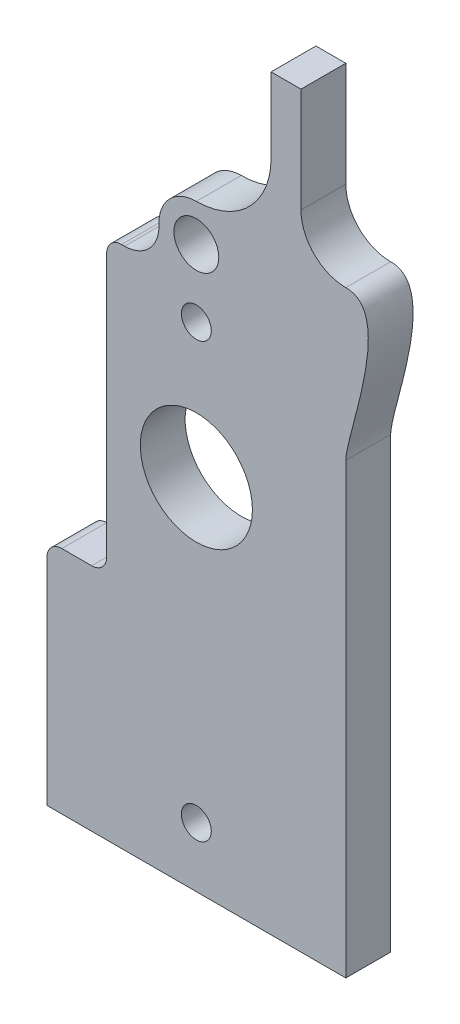
SolidWorks part; units mm, degrees
ref_plane "Alzado" through (0, 0, 0) normal (0, 0, 1) x (1, 0, 0)
ref_plane "Planta" through (0, 0, 0) normal (0, 1, 0) x (1, 0, 0)
ref_plane "Vista lateral" through (0, 0, 0) normal (1, 0, 0) x (0, 0, -1)
sketch "Croquis2" plane through (0, 0, 0) normal (0, 0, 1) x (1, 0, 0)
  line L0 (-10, 0) -> (10, 0) construction
  line L1 (10, 0) -> (10, 30)
  line L2 (10, 50) -> (-10, 50) construction
  line L3 (-10, 50) -> (-10, 0) construction
  line L4 (0, 50) -> (0, 40) construction
  line L5 (-10, 25) -> (-5, 25) construction
  line L6 (-5, 25) -> (-5, 45) construction
  line L7 (5, 45) -> (5, 50) construction
  line L8 (0, 40) -> (-5, 40) construction
  line L9 (0, 0) -> (0, 2) construction
  line L10 (6, 30) -> (6, 7) construction
  line L11 (6, 7) -> (-6, 7) construction
  line L12 (-6, 16.3832) -> (-6, 30)
  line L13 (-6, 30) -> (6, 30) construction
  line L14 (-6, 34) -> (-6, 30)
  line L15 (0, 2) -> (0, 4) construction
  line L16 (0, 4) -> (0, 7) construction
  line L17 (-10, 14.3832) -> (-10, 0)
  line L18 (-10, 0) -> (10, 0)
  line L19 (0, 30) -> (0, 33) construction
  line L20 (5, 45) -> (5, 50)
  line L21 (-5, 35) -> (-4.8, 35)
  line L22 (5, 50) -> (7, 50)
  line L23 (-6, 35) -> (-6, 30) construction
  line L24 (-2.5, 37.3) -> (-2.5, 37.5)
  line L25 (7, 50) -> (7, 43)
  line L26 (0, 24) -> (-8.2215, 26.1581) construction
  line L28 (-7, 15.3832) -> (-9, 15.3832)
  line L29 (0, 24) -> (-10.5, 24) construction
  line L30 (0, 30) -> (0, 24) construction
  arc A0 (0, 40) -> (5, 45) centre (0, 45) ccw
  circle A1 centre (0, 37.5) radius 1.5
  arc A2 (0, 40) -> (-2.5, 37.5) centre (0, 37.5) ccw
  arc A3 (7, 43) -> (10, 40) centre (10, 43) ccw
  circle A4 centre (0, 33) radius 1
  circle A5 centre (0, 4) radius 1
  arc A6 (-4.8, 35) -> (-2.5, 37.3) centre (-4.8, 37.3) ccw
  arc A7 (-6, 34) -> (-5, 35) centre (-5, 34) cw
  circle A8 centre (0, 24) radius 3.75
  circle A9 centre (0, 24) radius 10.5 construction
  circle A10 centre (0, 24) radius 8.5 construction
  arc A11 (-9, 15.3832) -> (-10, 14.3832) centre (-9, 14.3832) ccw
  arc A12 (-7, 15.3832) -> (-6, 16.3832) centre (-7, 16.3832) ccw
  spline S0 degree 3 poles (10, 40) (13.3825, 40) (10, 31.6044) (10, 30) knots 0 0 0 0 1 1 1 1
  point P39 (-10, 35)
  dimension "D3" = 1
  dimension "D4" = 2.3
  dimension "D5" = 1
  dimension "D1" = 50
  dimension "D2" = 20
extrude "Saliente-Extruir1" add sketch "Croquis2" along normal blind 3
